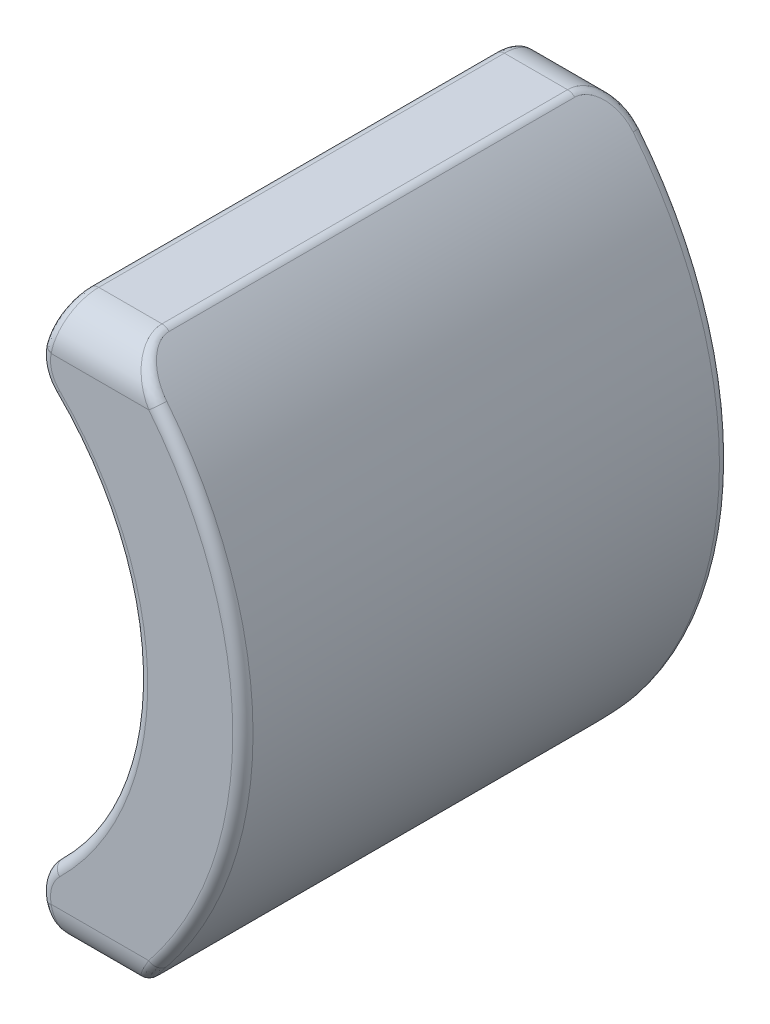
SolidWorks part; units mm, degrees
ref_plane "Front Plane" through (0, 0, 0) normal (0, 0, 1) x (1, 0, 0)
ref_plane "Top Plane" through (0, 0, 0) normal (0, 1, 0) x (1, 0, 0)
ref_plane "Right Plane" through (0, 0, 0) normal (1, 0, 0) x (0, 0, -1)
sketch "Sketch1" plane through (0, 0, 0) normal (0, 0, 1) x (1, 0, 0)
  line L0 (0, 0) -> (9.63, 0) construction
  line L1 (6.7381, -6.88) -> (4.8781, -6.88)
  line L2 (4.8781, -6.88) -> (4.5318, -5.38)
  line L3 (6.7381, 6.88) -> (4.8781, 6.88)
  line L4 (4.8781, 6.88) -> (4.5318, 5.38)
  arc A0 (6.7381, 6.88) -> (6.7381, -6.88) centre (0, 0) cw
  arc A1 (4.5318, 5.38) -> (4.5318, -5.38) centre (0, 0) cw
  point P6 (9.63, 0)
  dimension "D1" = 9.63
  dimension "D2" = 6.88
  dimension "D3" = 103
  dimension "D4" = 1.86
  dimension "D5" = 1.5
extrude "Boss-Extrude1" add sketch "Sketch1" along normal blind 12
fillet "Fillet1" radius 1 2 edges at (4.5318, -5.38, 6) (4.5318, 5.38, 6)
fillet "Fillet2" radius 1 4 edges at (5.8081, 6.88, 0) (5.8081, -6.88, 0) (5.8081, -6.88, 12) (5.8081, 6.88, 12)
fillet "Fillet3" radius 0.25 24 edges at (4.6879, 5.4113, 0) (4.8161, 6.6112, 0.3178) (4.8781, 6.88, 6) (4.8161, 6.6112, 11.6822) (4.6879, 5.4113, 12) (4.6879, -5.4113, 12) (4.8161, -6.6112, 11.6822) (4.8781, -6.88, 6) (4.8161, -6.6112, 0.3178) (4.6879, -5.4113, 0) (6.8685, -6.7498, 0.5066) (6.7381, -6.88, 6) (6.9882, -6.6258, 11.6661) (9.63, 0, 12) (6.8685, 6.7498, 11.4934) (6.7381, 6.88, 6) (6.9882, 6.6258, 0.3339) (9.63, 0, 0) (7.0343, 0, 12) (7.0343, 0, 0)
